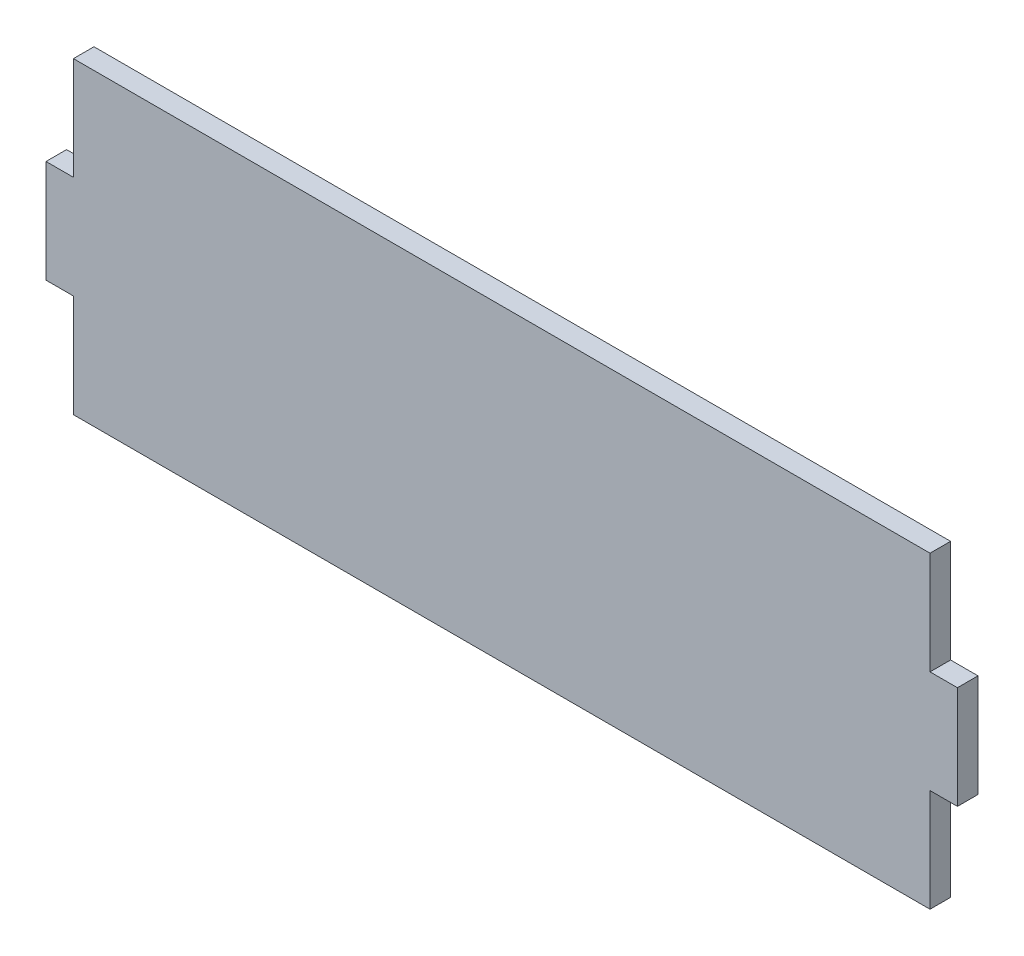
SolidWorks part; units mm, degrees
ref_plane "Front Plane" through (0, 0, 0) normal (0, 0, 1) x (1, 0, 0)
ref_plane "Top Plane" through (0, 0, 0) normal (0, 1, 0) x (1, 0, 0)
ref_plane "Right Plane" through (0, 0, 0) normal (1, 0, 0) x (0, 0, -1)
sketch "Sketch1" plane through (0, 0, 0) normal (0, 0, 1) x (1, 0, 0)
  line L1 (0, 0) -> (-125, 0)
  line L2 (0, 0) -> (0, 45)
  line L3 (0, 45) -> (-125, 45)
  line L4 (-125, 0) -> (-125, 45)
  dimension "D1" = 125
  dimension "D2" = 45
extrude "Boss-Extrude1" add sketch "Sketch1" along normal blind 3
sketch "Sketch2" plane through (0, 0, 3) normal (0, 0, 1) x (1, 0, 0)
  line L4 (4, 15) -> (4, 30)
  line L5 (0, 30) -> (4, 30)
  line L6 (0, 0) -> (0, 45) construction
  line L7 (0, 15) -> (4, 15)
  line L8 (-62.5, 45) -> (-62.5, 0) construction
  line L9 (0, 45) -> (-125, 45) construction
  line L11 (-125, 0) -> (0, 0) construction
  line L16 (-125, 30) -> (-125, 15)
  line L17 (0, 30) -> (0, 15)
  line L18 (-125, 15) -> (-129, 15)
  line L19 (-125, 30) -> (-129, 30)
  line L20 (-129, 15) -> (-129, 30)
  dimension "D3" = 15
extrude "Boss-Extrude2" add sketch "Sketch2" against normal blind 3
